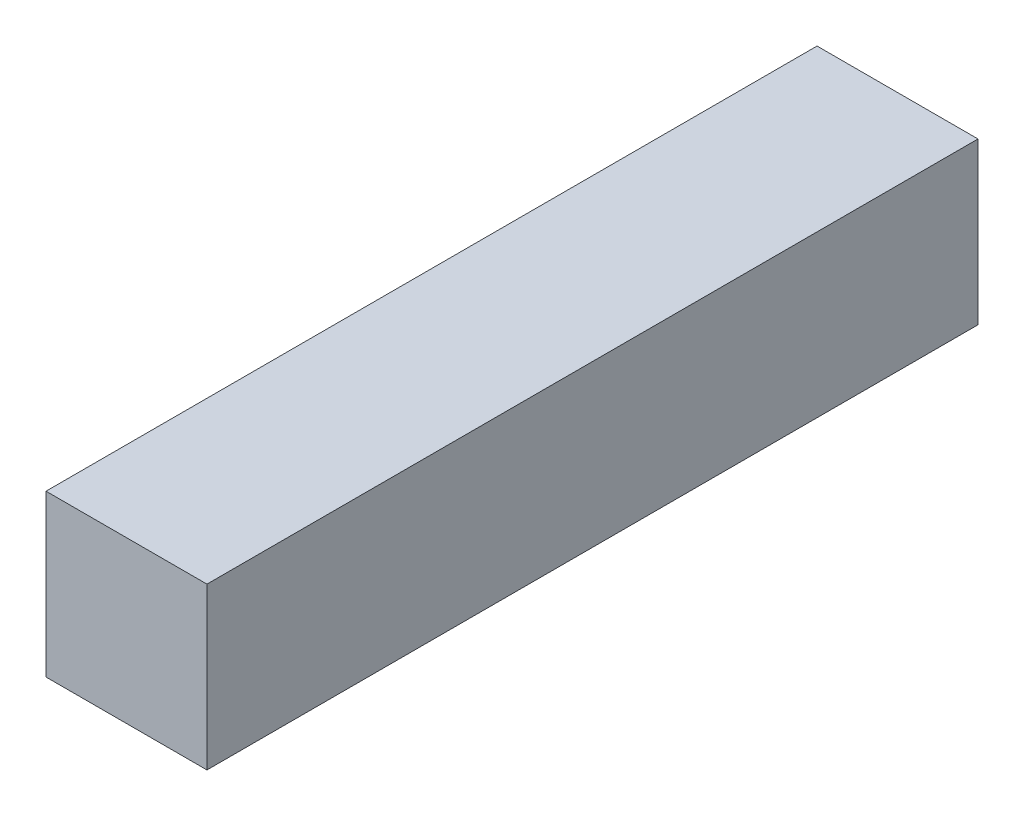
SolidWorks part; units mm, degrees
ref_plane "Front Plane" through (0, 0, 0) normal (0, 0, 1) x (1, 0, 0)
ref_plane "Top Plane" through (0, 0, 0) normal (0, 1, 0) x (1, 0, 0)
ref_plane "Right Plane" through (0, 0, 0) normal (1, 0, 0) x (0, 0, -1)
sketch "Sketch1" plane through (0, 0, 0) normal (0, 0, 1) x (1, 0, 0)
  line L1 (-8.35, -8.35) -> (8.35, -8.35)
  line L2 (-8.35, -8.35) -> (-8.35, 8.35)
  line L3 (-8.35, 8.35) -> (8.35, 8.35)
  line L4 (8.35, -8.35) -> (8.35, 8.35)
  line L5 (-8.35, -8.35) -> (8.35, 8.35) construction
  line L6 (-8.35, 8.35) -> (8.35, -8.35) construction
  point P0 (0, 0)
  dimension "D1" = 16.7
  dimension "D2" = 16.7
extrude "Boss-Extrude1" add sketch "Sketch1" along normal mid plane 80
